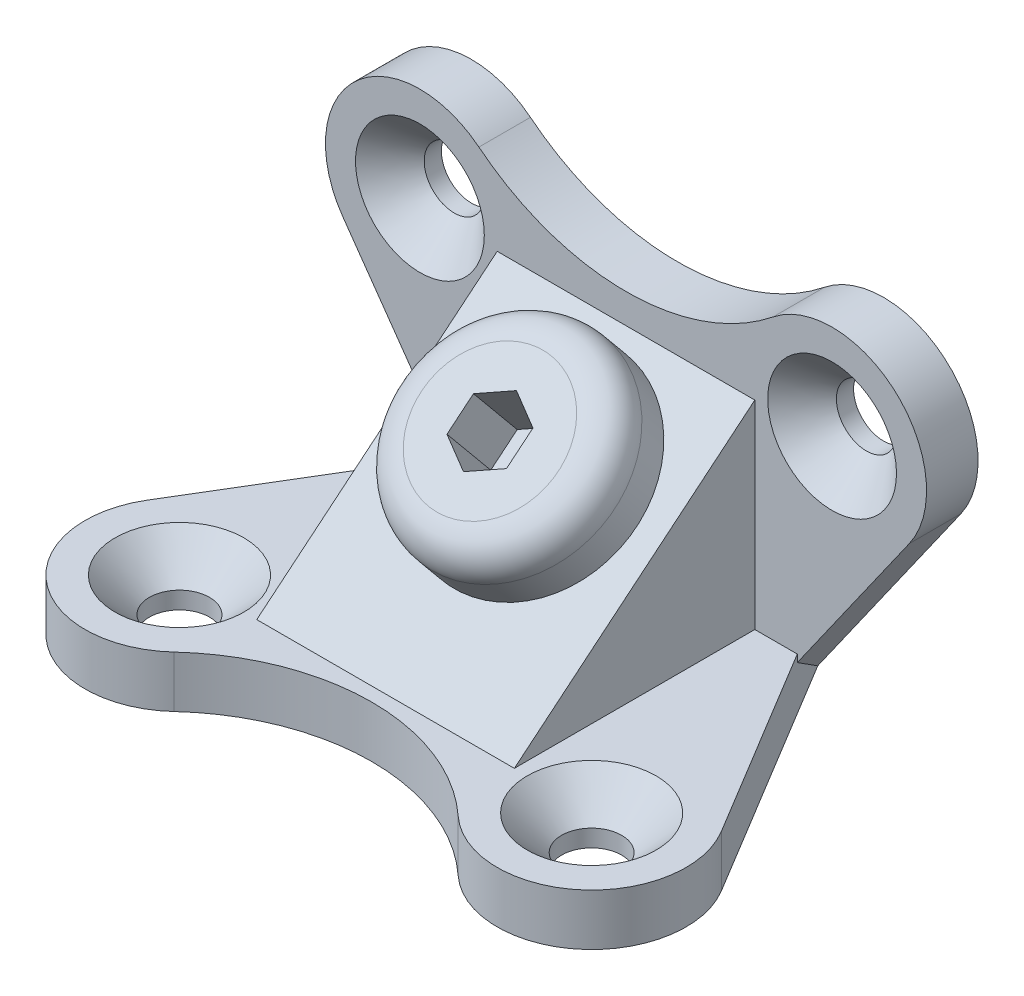
SolidWorks part; units mm, degrees
material "锌 AC41A 合金，作为铸件"
ref_plane "前视基准面" through (0, 0, 0) normal (0, 0, 1) x (1, 0, 0)
ref_plane "上视基准面" through (0, 0, 0) normal (0, 1, 0) x (1, 0, 0)
ref_plane "右视基准面" through (0, 0, 0) normal (1, 0, 0) x (0, 0, -1)
sketch "草图1" plane through (0, 0, 0) normal (0, 0, 1) x (1, 0, 0)
  line L0 (0, 0) -> (0, 30) construction
  line L1 (8.1628, 0) -> (-8.1628, 0)
  line L2 (-8.1628, 0) -> (-16.4967, 11.833)
  line L3 (8.1628, 0) -> (16.4967, 11.833)
  arc A0 (-8.5642, 19.2948) -> (-16.4967, 11.833) centre (-12, 15) ccw
  circle A1 centre (-12, 15) radius 1.75
  arc A2 (-8.5642, 19.2948) -> (8.5642, 19.2948) centre (0, 30) ccw
  circle A3 centre (12, 15) radius 1.75
  arc A4 (8.5642, 19.2948) -> (16.4967, 11.833) centre (12, 15) cw
  dimension "D1" = 3.5
  dimension "D3" = 11
  dimension "D2" = 24
  dimension "D4" = 15
  dimension "D5" = 30
extrude "凸台-拉伸1" add sketch "草图1" along normal blind 3
sketch "草图2" plane through (0, 0, 0) normal (0, -1, 0) x (1, 0, 0)
  line L0 (0, 0) -> (0, 30) construction
  line L1 (8.1628, 0) -> (-8.1628, 0)
  line L2 (-8.1628, 0) -> (-16.7087, 14.1578)
  line L3 (8.1628, 0) -> (16.7087, 14.1578)
  arc A0 (-8.2695, 21.0414) -> (-16.7087, 14.1578) centre (-12, 17) ccw
  circle A1 centre (-12, 17) radius 1.75
  arc A2 (-8.2695, 21.0414) -> (8.2695, 21.0414) centre (0, 30) ccw
  circle A3 centre (12, 17) radius 1.75
  arc A4 (8.2695, 21.0414) -> (16.7087, 14.1578) centre (12, 17) cw
  dimension "D1" = 11
  dimension "3.5" = 3.5
  dimension "D3" = 24
  dimension "D4" = 17
  dimension "D5" = 30
extrude "凸台-拉伸2" add sketch "草图2" against normal blind 3
sketch "草图3" plane through (0, 0, 0) normal (1, 0, 0) x (0, 0, -1)
  line L0 (-3, 3) -> (-17, 3)
  line L1 (-3, 3) -> (-14.1578, 3) construction
  line L2 (-17, 3) -> (-3, 14.5712)
  line L3 (-3, 2.5712) -> (-3, 11.833) construction
  line L4 (-3, 14.5712) -> (-3, 3)
  dimension "D1" = 12
  dimension "D2" = 14
extrude "凸台-拉伸3" add sketch "草图3" along normal mid plane 15
sketch "草图4" plane through (0, 10.1304, 8.3729) normal (0, 0.7708, 0.6371) x (1, 0, 0)
  line L1 (0, 2) -> (-1.7321, 1)
  line L2 (-1.7321, 1) -> (-1.7321, -1)
  line L3 (-1.7321, -1) -> (0, -2)
  line L4 (0, -2) -> (1.7321, -1)
  line L5 (1.7321, -1) -> (1.7321, 1)
  line L6 (1.7321, 1) -> (0, 2)
  circle A0 centre (0, 0) radius 6
  circle A1 centre (0, 0) radius 1.7321 construction
  dimension "D1" = 12
  dimension "D2" = 2
extrude "凸台-拉伸4" add sketch "草图4" along normal blind 4
fillet "圆角1" radius 2 1 edges at (0, 9.3911, 15.546)
chamfer "倒角1" distance 2 angle 45 4 edges at (-12, 3, 15.25) (12, 3, 18.75) (10.25, 15, 3) (-10.25, 15, 3)
